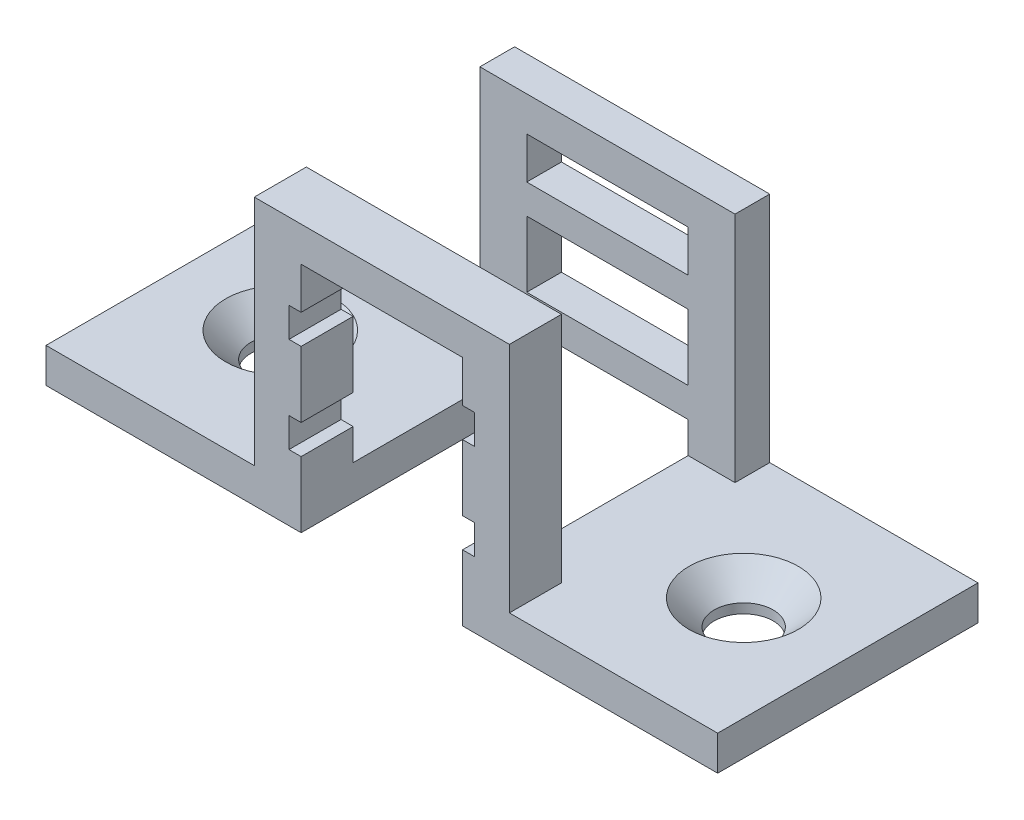
SolidWorks part; units mm, degrees
ref_plane "Front Plane" through (0, 0, 0) normal (0, 0, 1) x (1, 0, 0)
ref_plane "Top Plane" through (0, 0, 0) normal (0, 1, 0) x (1, 0, 0)
ref_plane "Right Plane" through (0, 0, 0) normal (1, 0, 0) x (0, 0, -1)
sketch "Sketch1" plane through (0, 0, 0) normal (0, 1, 0) x (1, 0, 0)
  line L1 (-7.35, -7.5) -> (7.35, -7.5)
  line L2 (-7.35, -7.5) -> (-7.35, 7.5)
  line L3 (-7.35, 7.5) -> (7.35, 7.5)
  line L4 (7.35, -7.5) -> (7.35, 7.5)
  line L5 (-7.35, -7.5) -> (7.35, 7.5) construction
  line L6 (-7.35, 7.5) -> (7.35, -7.5) construction
  point P0 (0, 0)
  dimension "D1" = 15
  dimension "D2" = 14.7
extrude "Boss-Extrude1" add sketch "Sketch1" along normal blind 15.4
sketch "Sketch2" plane through (0, 0, 7.5) normal (0, 0, 1) x (1, 0, 0)
  line L1 (-5.35, -1.2841) -> (5.35, -1.2841)
  line L2 (-5.35, -1.2841) -> (-5.35, 13.4)
  line L3 (-5.35, 13.4) -> (5.35, 13.4)
  line L4 (5.35, -1.2841) -> (5.35, 13.4)
  line L5 (-7.35, 15.4) -> (-7.35, 0) construction
  line L6 (-7.35, 15.4) -> (7.35, 15.4) construction
  line L7 (7.35, 15.4) -> (7.35, 0) construction
  dimension "D1" = 2
  dimension "D2" = 2
  dimension "D3" = 2
  dimension "D4" = 1.2841
extrude "Cut-Extrude1" cut sketch "Sketch2" against normal blind 13
sketch "Sketch4" plane through (0, 0, 7.5) normal (0, 0, 1) x (1, 0, 0)
  line L0 (-7.35, 15.4) -> (-7.35, 0) construction
  line L1 (-7.35, 5.5) -> (-4.65, 5.5)
  line L2 (-7.35, 5.5) -> (-7.35, 9.3)
  line L3 (-7.35, 9.3) -> (-4.65, 9.3)
  line L4 (-4.65, 5.5) -> (-4.65, 9.3)
  line L5 (-7.35, 11) -> (-4.65, 11)
  line L6 (-7.35, 11) -> (-7.35, 14.8)
  line L7 (-7.35, 14.8) -> (-4.65, 14.8)
  line L8 (-4.65, 11) -> (-4.65, 14.8)
  line L14 (0, 0) -> (0, 13.4) construction
  line L15 (-5.35, 0) -> (5.35, 0) construction
  line L16 (5.35, 13.4) -> (-5.35, 13.4) construction
  line L21 (4.65, 11) -> (4.65, 14.8)
  line L22 (7.35, 14.8) -> (4.65, 14.8)
  line L23 (7.35, 11) -> (7.35, 14.8)
  line L24 (7.35, 11) -> (4.65, 11)
  line L25 (4.65, 5.5) -> (4.65, 9.3)
  line L26 (7.35, 9.3) -> (4.65, 9.3)
  line L27 (7.35, 5.5) -> (7.35, 9.3)
  line L28 (7.35, 5.5) -> (4.65, 5.5)
  line L29 (-7.35, 3.8) -> (-4.65, 3.8)
  line L30 (-7.35, 3.8) -> (-7.35, 0)
  line L32 (-7.35, 0) -> (-4.65, 0)
  line L33 (-4.65, 3.8) -> (-4.65, 0)
  line L34 (4.65, 3.8) -> (4.65, 0)
  line L35 (7.35, 0) -> (4.65, 0)
  line L36 (7.35, 3.8) -> (7.35, 0)
  line L37 (7.35, 3.8) -> (4.65, 3.8)
  line L39 (-7.35, 0) -> (-5.35, 0) construction
  dimension "D1" = 3.8
  dimension "D2" = 2.7
  dimension "D3" = 1.7
  dimension "D5" = 3.8
  dimension "D6" = 1.7
extrude "Boss-Extrude2" add sketch "Sketch4" against normal blind 3
sketch "Sketch5" plane through (7.35, 0, 0) normal (1, 0, 0) x (0, 0, -1)
  line L1 (-4.5, 15.4) -> (5.5, 15.4)
  line L2 (-4.5, 15.4) -> (-4.5, 2)
  line L3 (-4.5, 2) -> (5.5, 2)
  line L4 (5.5, 15.4) -> (5.5, 2)
  line L6 (7.5, 15.4) -> (7.5, 0) construction
  line L7 (-7.5, 15.4) -> (-7.5, 0) construction
  line L9 (-7.5, 15.4) -> (7.5, 15.4) construction
  dimension "D1" = 2
  dimension "D2" = 2
  dimension "D3" = 3
extrude "Cut-Extrude2" cut sketch "Sketch5" against normal through all
sketch "Sketch6" plane through (0, 0, 7.5) normal (0, 0, 1) x (1, 0, 0)
  line L9 (-4.65, 9.3) -> (4.65, 9.3)
  line L10 (-4.65, 9.3) -> (-4.65, 5.5)
  line L11 (-4.65, 5.5) -> (4.65, 5.5)
  line L12 (4.65, 9.3) -> (4.65, 5.5)
  line L13 (-4.65, 3.8) -> (4.65, 3.8)
  line L14 (-4.65, 3.8) -> (-4.65, 0)
  line L15 (-4.65, 0) -> (4.65, 0)
  line L16 (4.65, 3.8) -> (4.65, 0)
  line L19 (4.65, 0) -> (7.35, 0) construction
  line L20 (4.65, 13.4) -> (4.65, 11) construction
  line L21 (-4.65, 13.4) -> (4.65, 13.4)
  line L22 (-4.65, 13.4) -> (-4.65, 11)
  line L23 (-4.65, 11) -> (4.65, 11)
  line L24 (4.65, 13.4) -> (4.65, 11)
  line L25 (4.65, 11) -> (5.35, 11) construction
extrude "Cut-Extrude3" cut sketch "Sketch6" against normal through all
sketch "Sketch7" plane through (-7.35, 0, 0) normal (-1, 0, 0) x (0, 0, 1)
  line L0 (-7.5, 0) -> (7.5, 0) construction
  line L1 (-7.5, 2) -> (7.5, 2)
  line L2 (-7.5, 2) -> (-7.5, 0)
  line L3 (-7.5, 0) -> (7.5, 0)
  line L4 (7.5, 2) -> (7.5, 0)
  line L5 (-7.5, 15.4) -> (-7.5, 0) construction
  line L6 (7.5, 15.4) -> (7.5, 0) construction
  dimension "D1" = 2
extrude "Boss-Extrude3" add sketch "Sketch7" along normal blind 12 and the other way blind 2.7
sketch "Sketch8" plane through (7.35, 0, 0) normal (1, 0, 0) x (0, 0, -1)
  line L0 (-7.5, 0) -> (7.5, 0) construction
  line L1 (-7.5, 2) -> (7.5, 2)
  line L2 (-7.5, 2) -> (-7.5, 0)
  line L3 (-7.5, 0) -> (7.5, 0)
  line L4 (7.5, 2) -> (7.5, 0)
  line L5 (-7.5, 15.4) -> (-7.5, 0) construction
extrude "Boss-Extrude4" add sketch "Sketch8" along normal blind 12 and the other way blind 2.7
sketch "Sketch9" plane through (0, 2, 0) normal (0, 1, 0) x (1, 0, 0)
  line L0 (-19.35, 0) -> (-4.65, 0) construction
  line L1 (-19.35, -7.5) -> (-19.35, 7.5) construction
  line L3 (-13.35, 7.5) -> (-13.35, -7.5) construction
  line L4 (-7.35, 7.5) -> (-19.35, 7.5) construction
  line L5 (-7.35, -7.5) -> (-19.35, -7.5) construction
  point P5 (-13.35, 0)
hole_wizard "CSK for M3 Flat Head Machine Screw1" positions "Sketch9" profile "Sketch10" countersink size "M3" standard "ANSI Metric" end condition through all
sketch "Sketch10" plane through (-13.35, 2, 0) normal (1, 0, 0) x (0, 0, 1)
  line L0 (0, 0) -> (0, 2)
  line L1 (0, 2) -> (1.7, 2)
  line L2 (1.7, 2) -> (1.7, 1.45)
  line L3 (1.7, 1.45) -> (3.15, 0)
  line L5 (3.15, 0) -> (0, 0)
  line L6 (-1.7, 1.45) -> (-3.15, 0) construction
  line L11 (0, -6.35) -> (0, 107.95) construction
  dimension "Thru Hole Dia." = 3.4
  dimension "Thru Hole Depth" = 2
  dimension "Near C'Sink Dia." = 6.3
  dimension "Near C'Sink Angle" = 90
sketch "Sketch11" plane through (0, 2, 0) normal (0, 1, 0) x (1, 0, 0)
  line L0 (13.35, 7.5) -> (13.35, -7.5) construction
  line L1 (7.35, 7.5) -> (19.35, 7.5) construction
  line L2 (7.35, -7.5) -> (19.35, -7.5) construction
  line L3 (19.35, 0) -> (4.65, 0) construction
  line L4 (19.35, 7.5) -> (19.35, -7.5) construction
  line L5 (4.65, 5.5) -> (4.65, -4.5) construction
  point P13 (13.35, 0)
hole_wizard "CSK for M3 Flat Head Machine Screw2" positions "Sketch11" profile "Sketch12" countersink size "M3" standard "ANSI Metric" end condition through all
sketch "Sketch12" plane through (13.35, 2, 0) normal (1, 0, 0) x (0, 0, 1)
  line L0 (0, 0) -> (0, 2)
  line L1 (0, 2) -> (1.7, 2)
  line L2 (1.7, 2) -> (1.7, 1.45)
  line L3 (1.7, 1.45) -> (3.15, 0)
  line L5 (3.15, 0) -> (0, 0)
  line L6 (-1.7, 1.45) -> (-3.15, 0) construction
  line L11 (0, -6.35) -> (0, 107.95) construction
  dimension "Thru Hole Dia." = 3.4
  dimension "Thru Hole Depth" = 2
  dimension "Near C'Sink Dia." = 6.3
  dimension "Near C'Sink Angle" = 90
